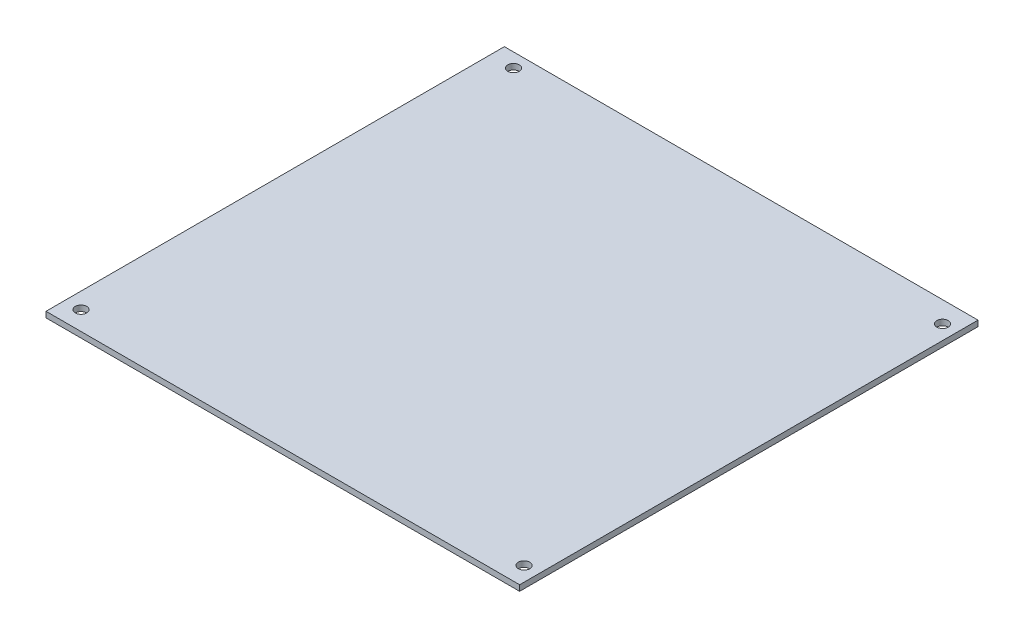
SolidWorks part; units mm, degrees
ref_plane "Front Plane" through (0, 0, 0) normal (0, 0, 1) x (1, 0, 0)
ref_plane "Top Plane" through (0, 0, 0) normal (0, 1, 0) x (1, 0, 0)
ref_plane "Right Plane" through (0, 0, 0) normal (1, 0, 0) x (0, 0, -1)
sketch "Sketch1" plane through (0, 0, 0) normal (0, 1, 0) x (1, 0, 0)
  line L1 (-62, 60) -> (62, 60)
  line L2 (-62, 60) -> (-62, -60)
  line L3 (-62, -60) -> (62, -60)
  line L4 (62, 60) -> (62, -60)
  line L5 (-62, 60) -> (62, -60) construction
  line L6 (-62, -60) -> (62, 60) construction
  point P0 (0, 0)
extrude "Boss-Extrude1" add sketch "Sketch1" along normal blind 1.5
sketch "Sketch2" plane through (0, 0, 0) normal (0, 1, 0) x (1, 0, 0)
  circle A0 centre (-55.9414, 56.3456) radius 1.5
  circle A1 centre (58.2049, 54.5021) radius 1.5
  circle A2 centre (-57.7848, -55.0521) radius 1.5
  circle A3 centre (58.2049, -55.0521) radius 1.5
extrude "Cut-Extrude7" cut sketch "Sketch2" along normal blind 8.5
